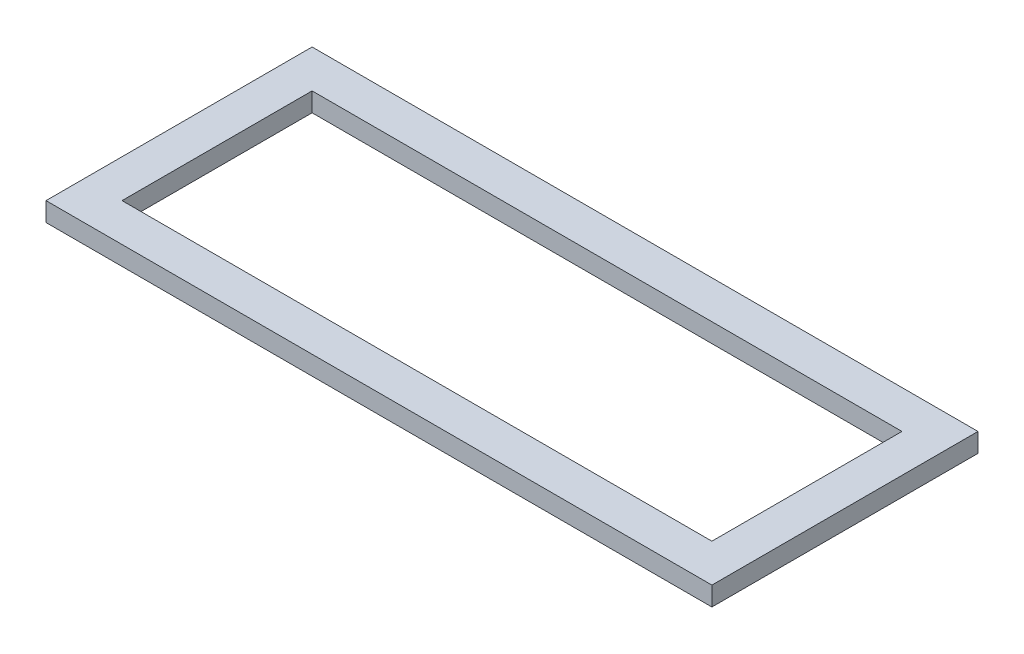
SolidWorks part; units mm, degrees
ref_plane "Front Plane" through (0, 0, 0) normal (0, 0, 1) x (1, 0, 0)
ref_plane "Top Plane" through (0, 0, 0) normal (0, 1, 0) x (1, 0, 0)
ref_plane "Right Plane" through (0, 0, 0) normal (1, 0, 0) x (0, 0, -1)
sketch "Sketch1" plane through (0, 0, 0) normal (0, 1, 0) x (1, 0, 0)
  line L0 (-29, -29) -> (-479, -29)
  line L1 (0, 0) -> (-508, 0)
  line L2 (0, 0) -> (0, -203)
  line L3 (0, -203) -> (-508, -203)
  line L4 (-508, 0) -> (-508, -203)
  line L5 (-479, -29) -> (-479, -174)
  line L6 (-29, -174) -> (-479, -174)
  line L7 (-29, -29) -> (-29, -174)
  dimension "D1" = 203
  dimension "D2" = 508
  dimension "D3" = 29
extrude "Boss-Extrude1" add sketch "Sketch1" along normal blind 14.5
